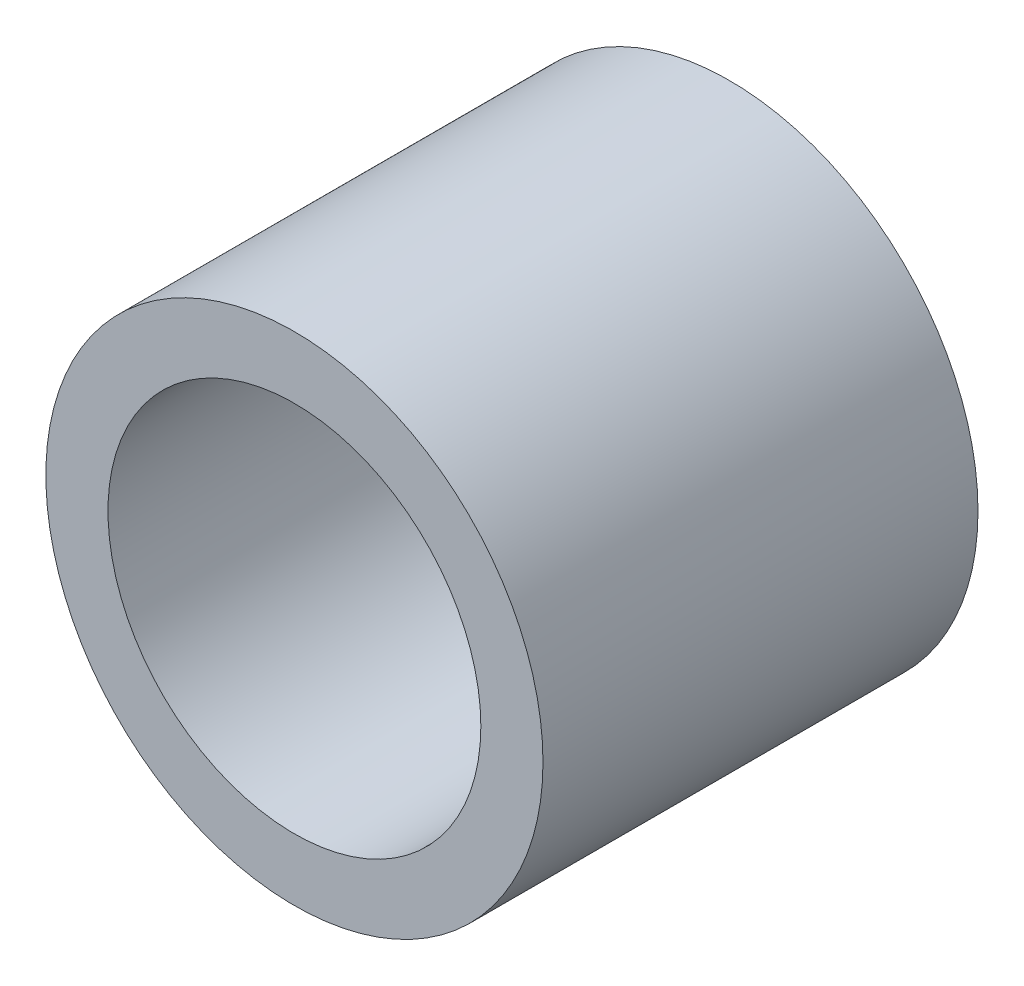
SolidWorks part; units mm, degrees
material "AISI 1020"
ref_plane "Ön Düzlem" through (0, 0, 0) normal (0, 0, 1) x (1, 0, 0)
ref_plane "Üst Düzlem" through (0, 0, 0) normal (0, 1, 0) x (1, 0, 0)
ref_plane "Sağ Düzlem" through (0, 0, 0) normal (1, 0, 0) x (0, 0, -1)
sketch "Çizim1" plane through (0, 0, 0) normal (0, 0, 1) x (1, 0, 0)
  circle A0 centre (0, 0) radius 40
  circle A1 centre (0, 0) radius 30
  dimension "D1" = 60
  dimension "D2" = 80
extrude "Yükseklik-Ekstrüzyon1" add sketch "Çizim1" along normal blind 70
